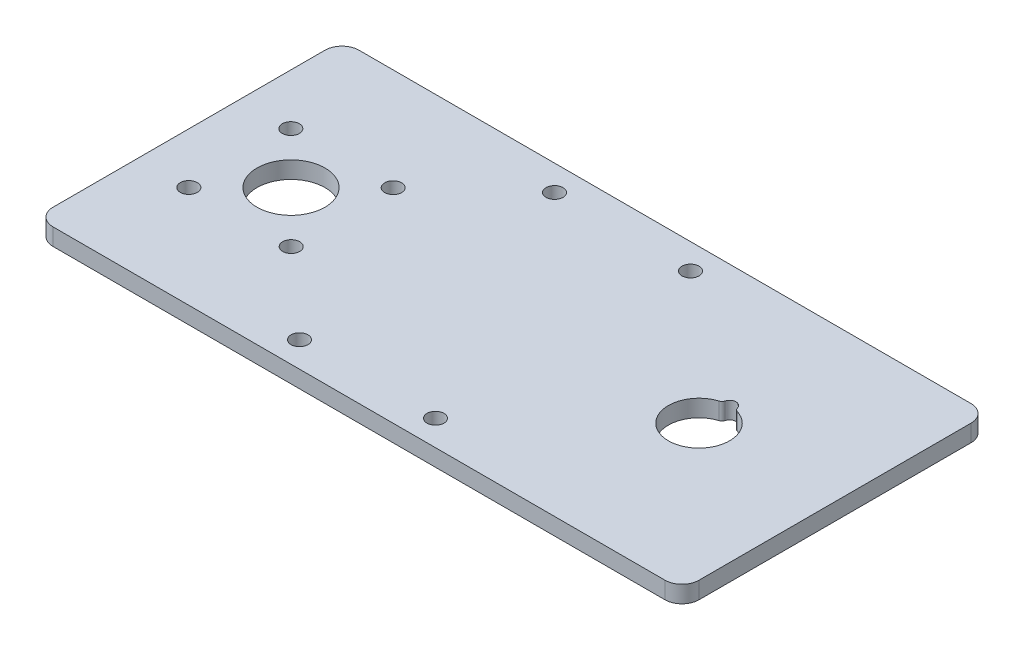
SolidWorks part; units mm, degrees
material "PC High Viscosity"
ref_plane "Front Plane" through (0, 0, 0) normal (0, 0, 1) x (1, 0, 0)
ref_plane "Top Plane" through (0, 0, 0) normal (0, 1, 0) x (1, 0, 0)
ref_plane "Right Plane" through (0, 0, 0) normal (1, 0, 0) x (0, 0, -1)
sketch "Sketch1" plane through (0, 0, 0) normal (0, 1, 0) x (1, 0, 0)
  line L1 (0, 0) -> (241.3, 0)
  line L2 (0, 0) -> (0, 114.3)
  line L3 (0, 114.3) -> (241.3, 114.3)
  line L4 (241.3, 0) -> (241.3, 114.3)
  circle A0 centre (38.1, 57.15) radius 12.7
  arc A1 (188.1317, 68.332) -> (192.8683, 68.332) centre (190.5, 57.15) ccw
  circle A2 centre (88.9, 104.775) radius 3.175
  circle A3 centre (139.7, 104.775) radius 3.175
  circle A4 centre (139.7, 9.525) radius 3.175
  circle A5 centre (88.9, 9.525) radius 3.175
  circle A6 centre (18.984, 76.2) radius 3.175
  circle A7 centre (18.984, 38.1) radius 3.175
  circle A8 centre (57.216, 38.1) radius 3.175
  circle A9 centre (57.216, 76.2) radius 3.175
  arc A10 (192.8683, 68.332) -> (188.1317, 68.332) centre (190.5, 68.58) ccw
  dimension "D1" = 25.4
  dimension "D2" = 22.86
  dimension "D9" = 6.35
  dimension "D15" = 6.35
  dimension "D19" = 4.7625
  dimension "D3" = 114.3
  dimension "D4" = 57.15
  dimension "D5" = 57.15
  dimension "D6" = 241.3
  dimension "D7" = 38.1
  dimension "D8" = 190.5
  dimension "D10" = 50.8
  dimension "D11" = 9.525
  dimension "D12" = 9.525
  dimension "D13" = 88.9
  dimension "D14" = 26.9875
  dimension "D16" = 26.9875
  dimension "D17" = 26.9875
  dimension "D18" = 38.1
extrude "Boss-Extrude1" add sketch "Sketch1" along normal blind 6.35
fillet "Fillet1" radius 6.35 4 edges at (0, 3.175, -114.3) (241.3, 3.175, -114.3) (241.3, 3.175, 0) (0, 3.175, 0)
fillet "Fillet2" radius 1.5875 2 edges at (192.8683, 3.175, -68.332) (188.1317, 3.175, -68.332)
